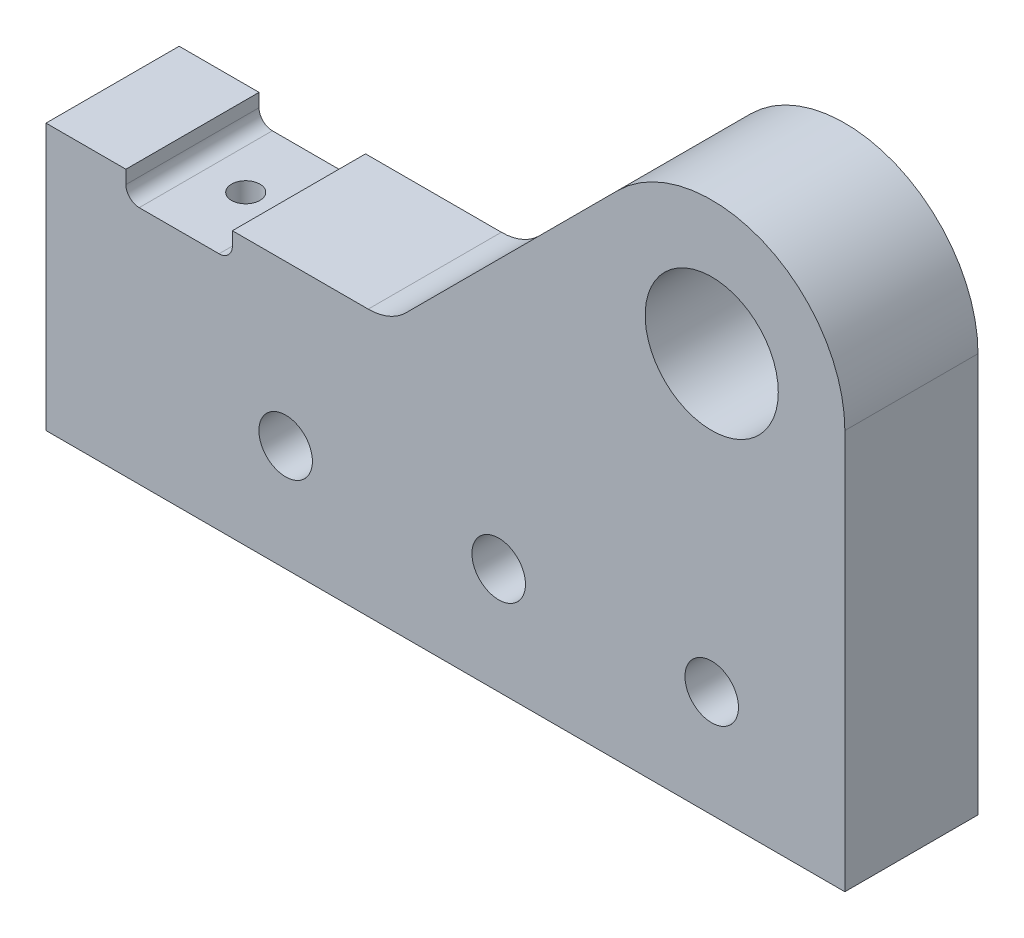
SolidWorks part; units mm, degrees
ref_plane "Front Plane" through (0, 0, 0) normal (0, 0, 1) x (1, 0, 0)
ref_plane "Top Plane" through (0, 0, 0) normal (0, 1, 0) x (1, 0, 0)
ref_plane "Right Plane" through (0, 0, 0) normal (1, 0, 0) x (0, 0, -1)
sketch "Sketch1" plane through (0, 0, 0) normal (0, 0, 1) x (1, 0, 0)
  line L0 (38.1, 12.7) -> (38.1, 25.4)
  line L1 (-38.1, -12.7) -> (38.1, -12.7)
  line L2 (-38.1, -12.7) -> (-38.1, 12.7)
  line L3 (-38.1, 12.7) -> (-30.48, 12.7)
  line L4 (38.1, -12.7) -> (38.1, 12.7)
  line L5 (-38.1, -12.7) -> (38.1, 12.7) construction
  line L6 (-38.1, 12.7) -> (38.1, -12.7) construction
  line L7 (-3.7726, 14.1879) -> (16.4197, 34.3803)
  line L8 (-30.48, 12.7) -> (-30.48, 11.43)
  line L9 (-29.21, 10.16) -> (-21.59, 10.16)
  line L10 (-20.32, 11.43) -> (-20.32, 12.7)
  line L11 (-20.32, 12.7) -> (-7.3647, 12.7)
  circle A1 centre (25.4, 25.4) radius 6.35
  arc A2 (-3.7726, 14.1879) -> (-7.3647, 12.7) centre (-7.3647, 17.78) cw
  arc A3 (16.4197, 34.3803) -> (38.1, 25.4) centre (25.4, 25.4) cw
  arc A4 (-29.21, 10.16) -> (-30.48, 11.43) centre (-29.21, 11.43) cw
  arc A5 (-21.59, 10.16) -> (-20.32, 11.43) centre (-21.59, 11.43) ccw
  point P0 (0, 0)
  point P9 (0, 0)
  dimension "D4" = 45
  dimension "D5" = 12.7
  dimension "D2" = 5.08
  dimension "D8" = 25.4
  dimension "D9" = 12.7
  dimension "D10" = 1.27
  dimension "D11" = 1.27
  dimension "D1" = 25.4
  dimension "D3" = 76.2
  dimension "D6" = 12.7
  dimension "D7" = 38.1
  dimension "D12" = 7.62
extrude "Boss-Extrude1" add sketch "Sketch1" along normal blind 12.7
sketch "Sketch3" plane through (0, 0, 12.7) normal (0, 0, 1) x (1, 0, 0)
  line L0 (-38.1, -12.7) -> (38.1, -12.7) construction
  line L1 (38.1, -12.7) -> (38.1, 25.4) construction
  point P0 (-15.24, -2.54)
  point P1 (5.08, -2.54)
  point P2 (25.4, -2.54)
  dimension "D1" = 10.16
  dimension "D2" = 53.34
  dimension "D3" = 33.02
  dimension "D4" = 12.7
hole_wizard "1/4-20 Tapped Hole1" positions "Sketch3" profile "Sketch4" tap size "1/4-20" standard "ANSI Inch" end condition through all
sketch "Sketch4" plane through (-15.24, -2.54, 12.7) normal (1, 0, 0) x (0, -1, 0)
  line L0 (0, 0) -> (0, 12.7)
  line L1 (0, 12.7) -> (2.5527, 12.7)
  line L2 (2.5527, 12.7) -> (2.5527, 0)
  line L5 (2.5527, 0) -> (0, 0)
  line L11 (0, -6.35) -> (0, 107.95) construction
  dimension "Thru Tap Drill Dia." = 5.1054
  dimension "Thru Tap Drill Depth" = 12.7
cosmetic thread "Hole Thread1" parameters "D2"=6.35
cosmetic thread "Hole Thread2" parameters "D2"=6.35
cosmetic thread "Hole Thread3" parameters "D2"=6.35
sketch "Sketch5" plane through (0, 10.16, 0) normal (0, 1, 0) x (1, 0, 0)
  line L0 (-38.1, -12.7) -> (-38.1, 0) construction
  line L1 (-21.59, -12.7) -> (-29.21, -12.7) construction
  point P0 (-25.4, -6.35)
  dimension "D1" = 12.7
  dimension "D2" = 6.35
hole_wizard "#6-32 Tapped Hole1" positions "Sketch5" profile "Sketch6" tap size "#6-32" standard "ANSI Inch"
cosmetic thread "Hole Thread4" parameters "D1"=7.112, "D2"=3.5052
sketch "Sketch6" plane through (-25.4, 10.16, 6.35) normal (1, 0, 0) x (0, 0, 1)
  line L0 (0, 0) -> (0, 10.2107)
  line L1 (0, 10.2107) -> (1.3525, 9.398)
  line L2 (1.3525, 9.398) -> (1.3525, 0)
  line L5 (1.3525, 0) -> (0, 0)
  line L10 (0, 10.2107) -> (-1.3526, 9.398) construction
  line L11 (0, -6.35) -> (0, 107.95) construction
  dimension "Tap Drill Dia." = 2.7051
  dimension "Tap Drill Depth" = 9.398
  dimension "Drill Angle" = 118
